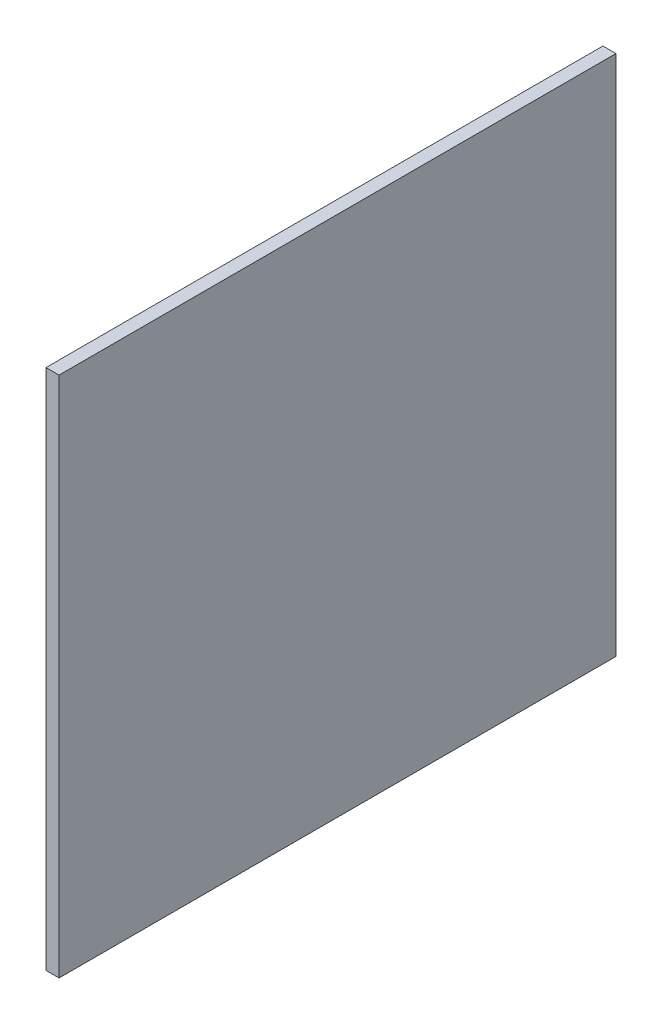
SolidWorks part; units mm, degrees
material "Pine"
ref_plane "Front Plane" through (0, 0, 0) normal (0, 0, 1) x (1, 0, 0)
ref_plane "Top Plane" through (0, 0, 0) normal (0, 1, 0) x (1, 0, 0)
ref_plane "Right Plane" through (0, 0, 0) normal (1, 0, 0) x (0, 0, -1)
sketch "Sketch1" plane through (0, 0, 0) normal (0, 0, 1) x (1, 0, 0)
  line L0 (-108.5345, -3.9032) -> (-108.5345, 758.0968)
  line L1 (-89.4845, -3.9032) -> (-89.4845, 758.0968)
  line L2 (-108.5345, -3.9032) -> (-89.4845, -3.9032)
  line L3 (-108.5345, 758.0968) -> (-89.4845, 758.0968)
  dimension "D1" = 19.05
extrude "Boss-Extrude1" add sketch "Sketch1" along normal blind 812.8
